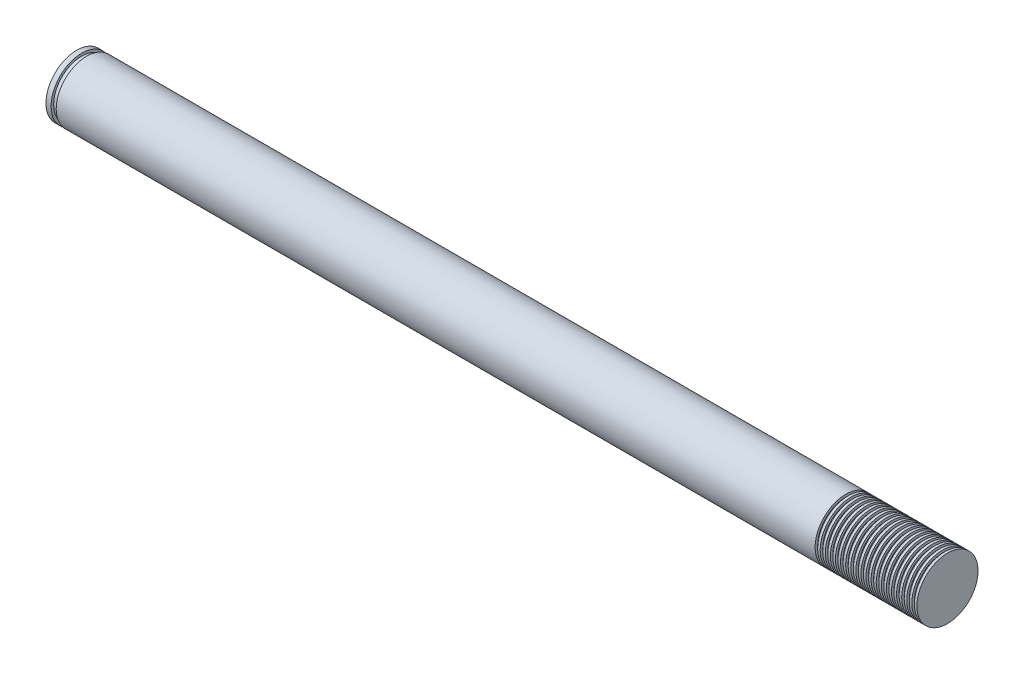
SolidWorks part; units mm, degrees
ref_plane "Front Plane" through (0, 0, 0) normal (0, 0, 1) x (1, 0, 0)
ref_plane "Top Plane" through (0, 0, 0) normal (0, 1, 0) x (1, 0, 0)
ref_plane "Right Plane" through (0, 0, 0) normal (1, 0, 0) x (0, 0, -1)
sketch "Sketch1" plane through (0, 0, 0) normal (0, 0, 1) x (1, 0, 0)
  line L0 (0, 0) -> (171, 0)
  line L1 (0, 0) -> (0, 6)
  line L2 (0, 6) -> (1, 6)
  line L3 (1, 6) -> (1, 5.5)
  line L4 (1, 5.5) -> (2, 5.5)
  line L5 (2, 5.5) -> (2, 6)
  line L6 (2, 6) -> (47, 6)
  line L7 (47, 6) -> (121, 6)
  line L8 (121, 6) -> (151, 6)
  line L9 (151, 6) -> (151, 5.5)
  line L10 (151, 5.5) -> (151.5, 5.5)
  line L11 (151.5, 5.5) -> (151.5, 6)
  line L12 (151.5, 6) -> (152, 6)
  line L13 (152, 6) -> (152, 5.5)
  line L14 (152, 5.5) -> (152.5, 5.5)
  line L15 (152.5, 5.5) -> (152.5, 6)
  line L16 (153.5, 5.5) -> (153.5, 6)
  line L17 (153, 6) -> (153, 5.5)
  line L18 (152.5, 6) -> (153, 6)
  line L19 (153, 5.5) -> (153.5, 5.5)
  line L20 (154.5, 5.5) -> (154.5, 6)
  line L21 (154, 6) -> (154, 5.5)
  line L22 (153.5, 6) -> (154, 6)
  line L23 (154, 5.5) -> (154.5, 5.5)
  line L24 (155.5, 5.5) -> (155.5, 6)
  line L25 (155, 6) -> (155, 5.5)
  line L26 (154.5, 6) -> (155, 6)
  line L27 (155, 5.5) -> (155.5, 5.5)
  line L28 (156.5, 5.5) -> (156.5, 6)
  line L29 (156, 6) -> (156, 5.5)
  line L30 (155.5, 6) -> (156, 6)
  line L31 (156, 5.5) -> (156.5, 5.5)
  line L32 (157.5, 5.5) -> (157.5, 6)
  line L33 (157, 6) -> (157, 5.5)
  line L34 (156.5, 6) -> (157, 6)
  line L35 (157, 5.5) -> (157.5, 5.5)
  line L36 (158.5, 5.5) -> (158.5, 6)
  line L37 (158, 6) -> (158, 5.5)
  line L38 (157.5, 6) -> (158, 6)
  line L39 (158, 5.5) -> (158.5, 5.5)
  line L40 (159.5, 5.5) -> (159.5, 6)
  line L41 (159, 6) -> (159, 5.5)
  line L42 (158.5, 6) -> (159, 6)
  line L43 (159, 5.5) -> (159.5, 5.5)
  line L44 (160.5, 5.5) -> (160.5, 6)
  line L45 (160, 6) -> (160, 5.5)
  line L46 (159.5, 6) -> (160, 6)
  line L47 (160, 5.5) -> (160.5, 5.5)
  line L48 (161.5, 5.5) -> (161.5, 6)
  line L49 (161, 6) -> (161, 5.5)
  line L50 (160.5, 6) -> (161, 6)
  line L51 (161, 5.5) -> (161.5, 5.5)
  line L52 (162.5, 5.5) -> (162.5, 6)
  line L53 (162, 6) -> (162, 5.5)
  line L54 (161.5, 6) -> (162, 6)
  line L55 (162, 5.5) -> (162.5, 5.5)
  line L56 (163.5, 5.5) -> (163.5, 6)
  line L57 (163, 6) -> (163, 5.5)
  line L58 (162.5, 6) -> (163, 6)
  line L59 (163, 5.5) -> (163.5, 5.5)
  line L60 (164.5, 5.5) -> (164.5, 6)
  line L61 (164, 6) -> (164, 5.5)
  line L62 (163.5, 6) -> (164, 6)
  line L63 (164, 5.5) -> (164.5, 5.5)
  line L64 (165.5, 5.5) -> (165.5, 6)
  line L65 (165, 6) -> (165, 5.5)
  line L66 (164.5, 6) -> (165, 6)
  line L67 (165, 5.5) -> (165.5, 5.5)
  line L68 (166.5, 5.5) -> (166.5, 6)
  line L69 (166, 6) -> (166, 5.5)
  line L70 (165.5, 6) -> (166, 6)
  line L71 (166, 5.5) -> (166.5, 5.5)
  line L72 (167.5, 5.5) -> (167.5, 6)
  line L73 (167, 6) -> (167, 5.5)
  line L74 (166.5, 6) -> (167, 6)
  line L75 (167, 5.5) -> (167.5, 5.5)
  line L76 (168.5, 5.5) -> (168.5, 6)
  line L77 (168, 6) -> (168, 5.5)
  line L78 (167.5, 6) -> (168, 6)
  line L79 (168, 5.5) -> (168.5, 5.5)
  line L80 (169.5, 5.5) -> (169.5, 6)
  line L81 (169, 6) -> (169, 5.5)
  line L82 (168.5, 6) -> (169, 6)
  line L83 (169, 5.5) -> (169.5, 5.5)
  line L84 (170.5, 5.5) -> (170.5, 6)
  line L85 (170, 6) -> (170, 5.5)
  line L86 (169.5, 6) -> (170, 6)
  line L87 (170, 5.5) -> (170.5, 5.5)
  line L88 (171, 5.5) -> (171, 0)
  line L89 (171, 6) -> (171, 5.5)
  line L90 (170.5, 6) -> (171, 6)
revolve "Revolve1" add sketch "Sketch1" angle 360 about L0
